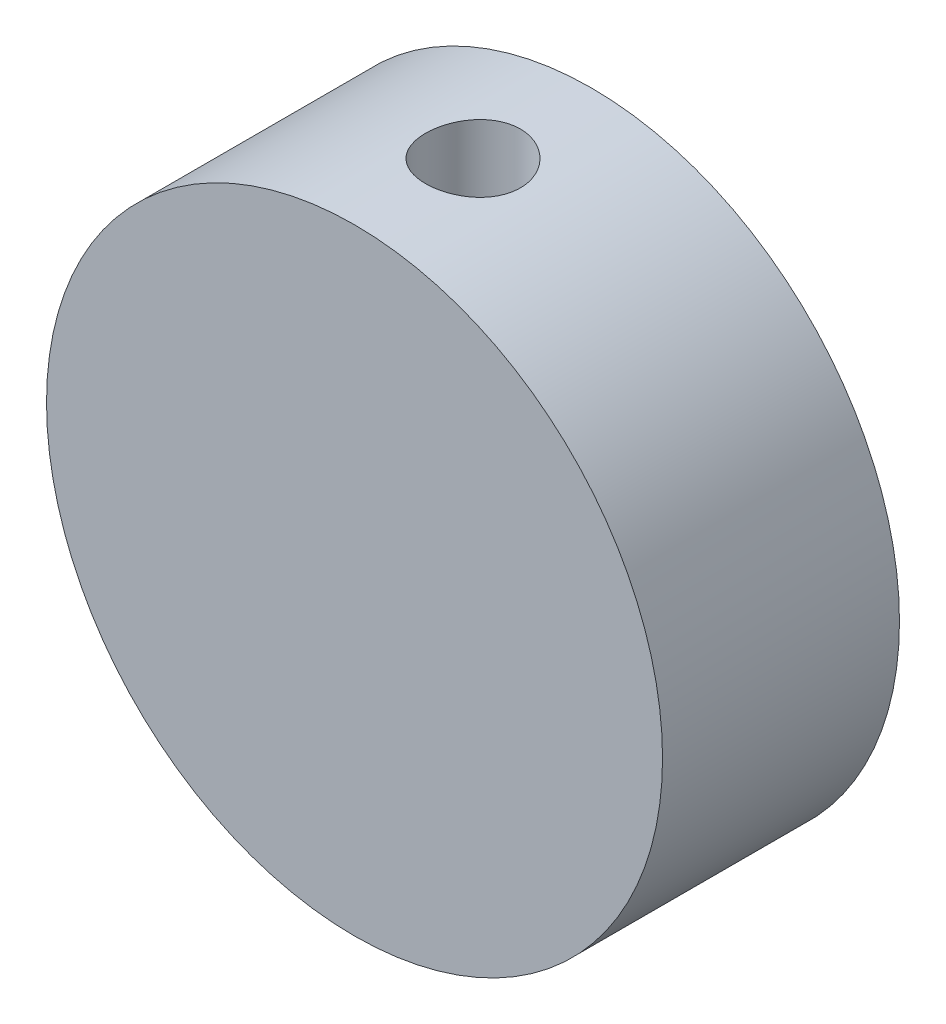
SolidWorks part; units mm, degrees
ref_plane "Front Plane" through (0, 0, 0) normal (0, 0, 1) x (1, 0, 0)
ref_plane "Top Plane" through (0, 0, 0) normal (0, 1, 0) x (1, 0, 0)
ref_plane "Right Plane" through (0, 0, 0) normal (1, 0, 0) x (0, 0, -1)
sketch "profile:outer" plane through (0, 0, 0) normal (0, 0, 1) x (1, 0, 0)
  circle A0 centre (0, 0) radius 26
extrude "feature:cylinder" add sketch "profile:outer" along normal mid plane 20 separate body
sketch "profile:bore" plane through (0, 0, 0) normal (0, 1, 0) x (1, 0, 0)
  circle A0 centre (0, 0) radius 4
extrude "feature:cross-bore" cut sketch "profile:bore" along normal mid plane 80
